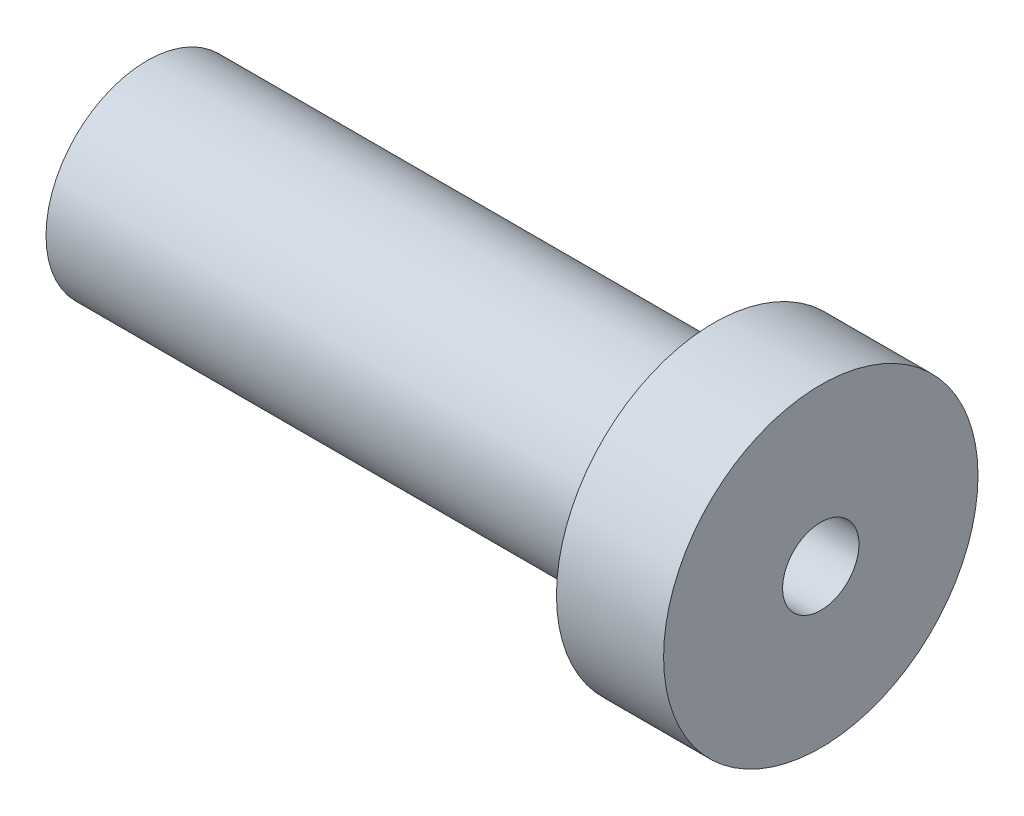
SolidWorks part; units mm, degrees
material "Alumina"
ref_plane "Front Plane" through (0, 0, 0) normal (0, 0, 1) x (1, 0, 0)
ref_plane "Top Plane" through (0, 0, 0) normal (0, 1, 0) x (1, 0, 0)
ref_plane "Right Plane" through (0, 0, 0) normal (1, 0, 0) x (0, 0, -1)
sketch "Sketch1" plane through (0, 0, 0) normal (0, 0, 1) x (1, 0, 0)
  line L0 (0, 0) -> (0, 4.5)
  line L1 (0, 4.5) -> (25.2299, 4.5)
  line L2 (25.2299, 4.5) -> (25.2299, 7)
  line L3 (25.2299, 7) -> (30, 7)
  line L4 (30, 7) -> (30, 0)
  line L5 (30, 0) -> (0, 0)
  line L6 (0, 0) -> (-5.9552, 0) construction
  line L7 (-5.9552, 0) -> (25.4515, 0) construction
  point P8 (0, 0)
  dimension "D1" = 30
  dimension "D2" = 7
  dimension "D3" = 4.5
revolve "Revolve1" add sketch "Sketch1" angle 360 about L7
sketch "Sketch2" plane through (0, 0, 0) normal (1, 0, 0) x (0, 0, -1)
  circle A0 centre (0, 0) radius 1.7
  dimension "D1" = 3.4
extrude "Cut-Extrude2" cut sketch "Sketch2" along normal through all
